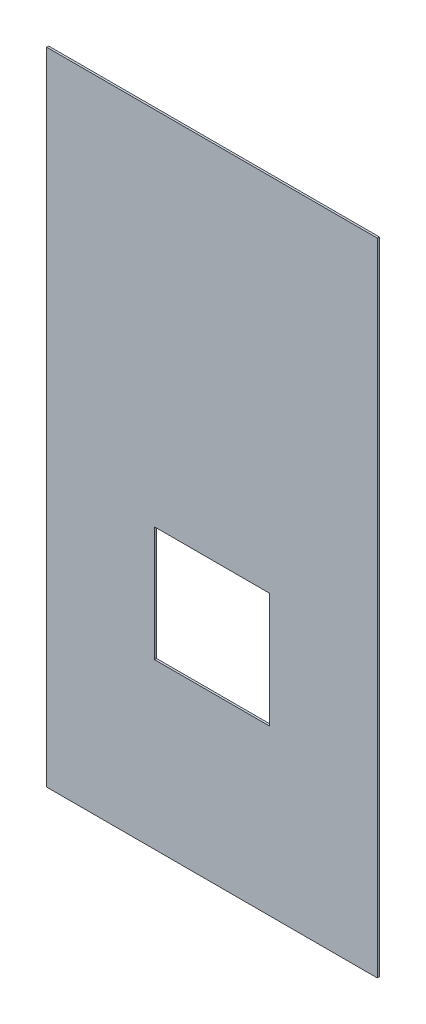
SolidWorks part; units mm, degrees
ref_plane "Front Plane" through (0, 0, 0) normal (0, 0, 1) x (1, 0, 0)
ref_plane "Top Plane" through (0, 0, 0) normal (0, 1, 0) x (1, 0, 0)
ref_plane "Right Plane" through (0, 0, 0) normal (1, 0, 0) x (0, 0, -1)
sketch "Sketch1" plane through (0, 0, 0) normal (0, 0, 1) x (1, 0, 0)
  line L1 (0, 0) -> (1022.35, 0)
  line L2 (0, 0) -> (0, 1981.2)
  line L3 (0, 1981.2) -> (1022.35, 1981.2)
  line L4 (1022.35, 0) -> (1022.35, 1981.2)
  line L5 (333.248, 863.6) -> (688.848, 863.6)
  line L6 (333.248, 863.6) -> (333.248, 508)
  line L7 (333.248, 508) -> (688.848, 508)
  line L8 (688.848, 863.6) -> (688.848, 508)
  dimension "D1" = 1022.35
  dimension "D2" = 1981.2
  dimension "D3" = 508
  dimension "D4" = 863.6
  dimension "D5" = 333.502
  dimension "D6" = 689.102
extrude "Boss-Extrude1" add sketch "Sketch1" along normal blind 6.35
